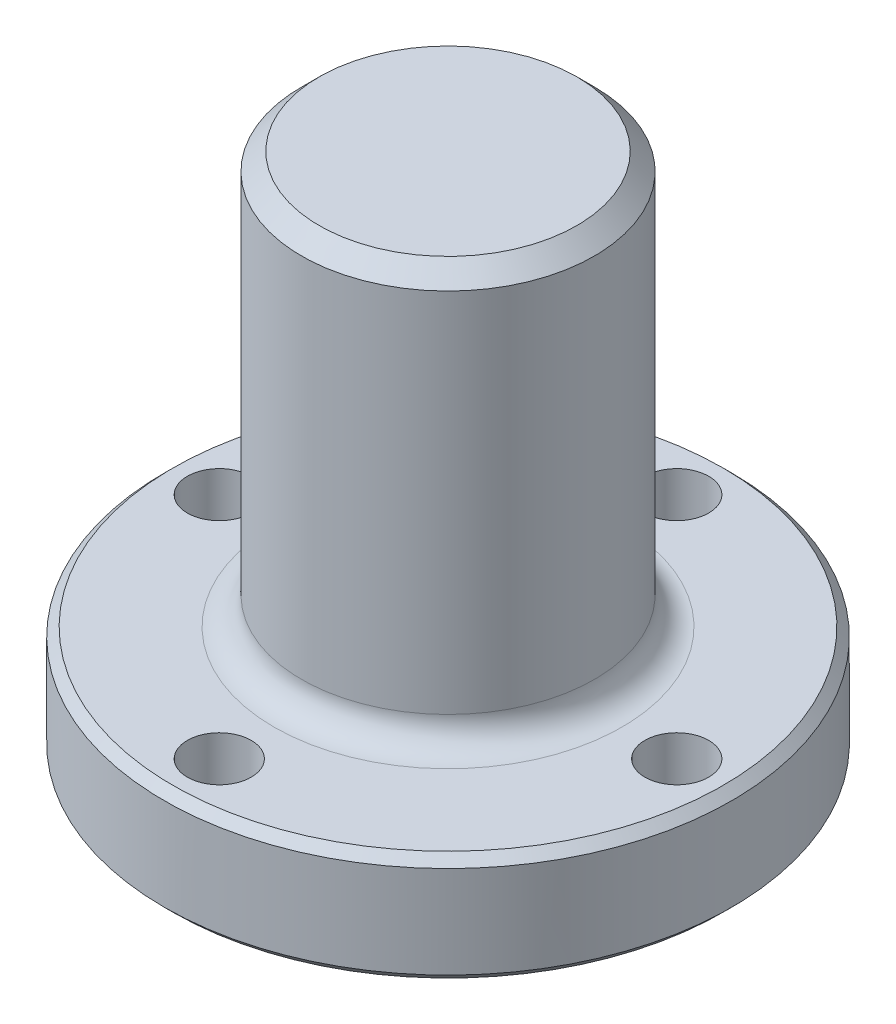
SolidWorks part; units mm, degrees
ref_plane "Front Plane" through (0, 0, 0) normal (1, 0, 0) x (0, 1, 0)
ref_plane "Top Plane" through (0, 0, 0) normal (0, 0, 1) x (0, 1, 0)
ref_plane "Right Plane" through (0, 0, 0) normal (0, 1, 0) x (-1, 0, 0)
sketch "Sketch1" plane through (0, 0, 0) normal (0, 0, 1) x (0, 1, 0)
  line L0 (-25.0317, 0) -> (-25.0317, 8.7122)
  line L1 (-25.0317, 8.7122) -> (-20.2057, 8.7122)
  line L2 (-20.2057, 8.7122) -> (-20.2057, 24.6126)
  line L3 (-20.2057, 24.6126) -> (-10.6807, 24.6126)
  line L4 (-10.6807, 24.6126) -> (-10.6807, 12.7)
  line L5 (-10.6807, 12.7) -> (25.0317, 12.7)
  line L6 (25.0317, 12.7) -> (25.0317, 0)
  line L7 (25.0317, 0) -> (-25.0317, 0)
  line L8 (-50.4317, 0) -> (50.4317, 0) construction
revolve "Revolve1" add sketch "Sketch1" angle 360 about L8
fillet "Fillet1" radius 2.3876 1 edges at (0, -10.6807, -12.7)
chamfer "Chamfer1" distance 0.762 angle 45 3 edges at (0, -10.6807, -24.6126) (0, -20.2057, -24.6126) (0, -25.0317, -8.7122)
chamfer "Chamfer2" distance 1.524 angle 45 1 edges at (0, 25.0317, -12.7)
sketch "Sketch2" plane through (0, 0, 0) normal (0, 1, 0) x (-1, 0, 0)
  circle A0 centre (19.8374, 0) radius 2.7686
extrude "Cut-Extrude2" cut sketch "Sketch2" against normal up to next from offset 10.6807
sketch "Sketch3" plane through (0, 0, 0) normal (0, 1, 0) x (-1, 0, 0)
  circle A0 centre (0, 19.8374) radius 2.7686
  circle A1 centre (-19.8374, 0) radius 2.7686
  circle A2 centre (0, -19.8374) radius 2.7686
extrude "Cut-Extrude4" cut sketch "Sketch3" against normal up to next from offset 10.6807
